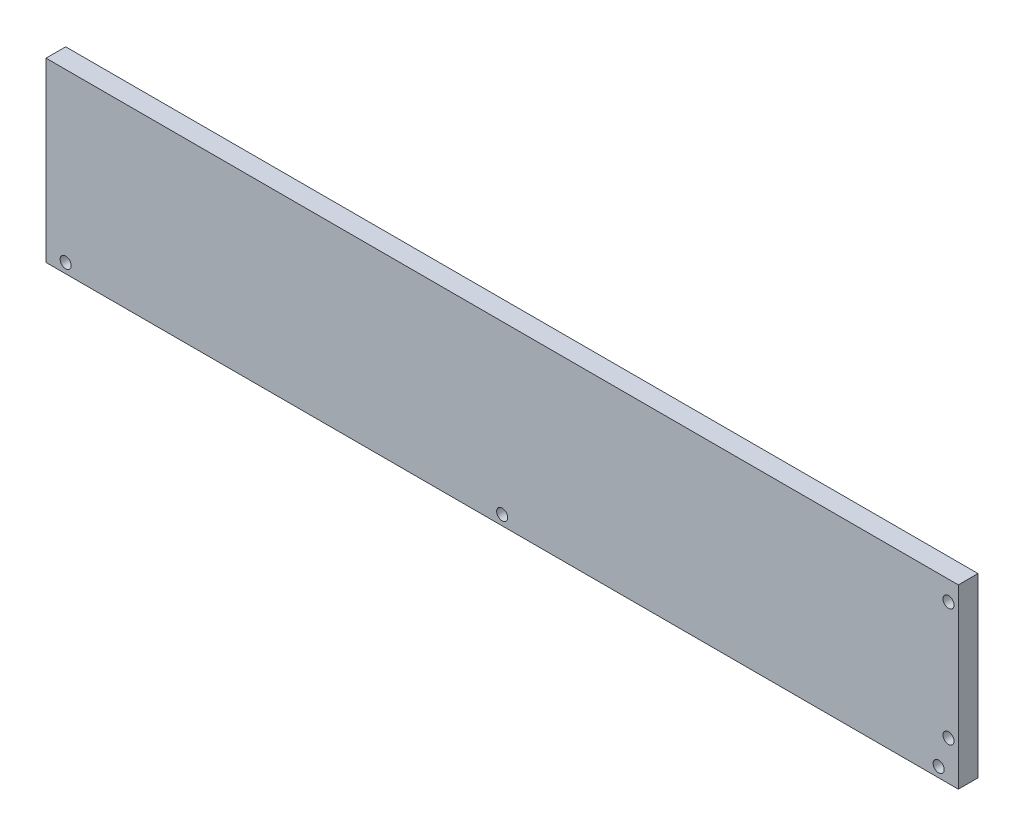
SolidWorks part; units mm, degrees
ref_plane "Front Plane" through (0, 0, 0) normal (0, 0, 1) x (1, 0, 0)
ref_plane "Top Plane" through (0, 0, 0) normal (0, 1, 0) x (1, 0, 0)
ref_plane "Right Plane" through (0, 0, 0) normal (1, 0, 0) x (0, 0, -1)
sketch "Sketch1" plane through (0, 0, 0) normal (0, 0, 1) x (1, 0, 0)
  line L0 (147.32, 3.175) -> (147.32, 0) construction
  line L1 (0, 0) -> (294.64, 0)
  line L2 (0, 0) -> (0, 57.15)
  line L3 (0, 57.15) -> (294.64, 57.15)
  line L4 (294.64, 0) -> (294.64, 57.15)
  line L5 (6.35, 3.175) -> (6.35, 0) construction
  circle A0 centre (6.35, 3.175) radius 1.7859
  circle A1 centre (147.32, 3.175) radius 1.7859
  circle A2 centre (288.29, 3.175) radius 1.7859
  circle A3 centre (291.465, 50.8) radius 1.7859
  circle A4 centre (291.465, 12.7) radius 1.7859
  dimension "D3" = 3.5719
  dimension "D6" = 3.5719
  dimension "D10" = 3.5719
  dimension "D13" = 3.5719
  dimension "D16" = 3.5719
  dimension "D1" = 57.15
  dimension "D2" = 294.64
  dimension "D4" = 3.175
  dimension "D5" = 3.175
  dimension "D7" = 6.35
  dimension "D8" = 6.35
  dimension "D9" = 3.175
  dimension "D11" = 3.175
  dimension "D12" = 6.35
  dimension "D14" = 3.175
  dimension "D15" = 12.7
extrude "Boss-Extrude1" add sketch "Sketch1" along normal blind 6.35
